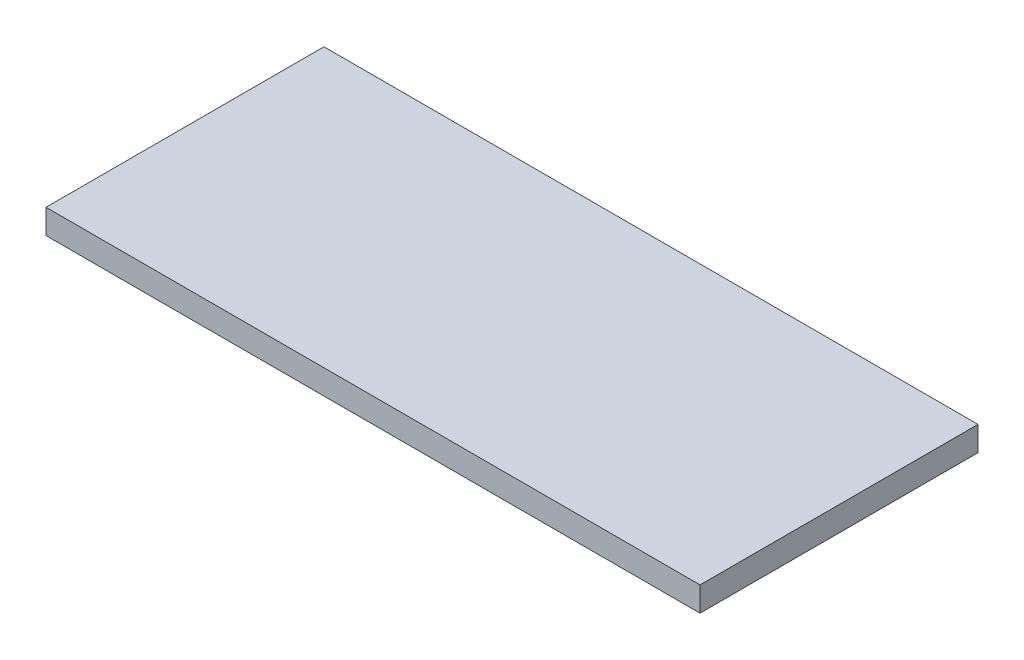
SolidWorks part; units mm, degrees
ref_plane "Front" through (0, 0, 0) normal (0, 0, 1) x (1, 0, 0)
ref_plane "Top" through (0, 0, 0) normal (0, 1, 0) x (1, 0, 0)
ref_plane "Right" through (0, 0, 0) normal (1, 0, 0) x (0, 0, -1)
sketch "Sketch1" plane through (0, 0, 0) normal (0, 1, 0) x (1, 0, 0)
  line L1 (-127, -53.975) -> (127, -53.975)
  line L2 (-127, -53.975) -> (-127, 53.975)
  line L3 (-127, 53.975) -> (127, 53.975)
  line L4 (127, -53.975) -> (127, 53.975)
  line L5 (-127, -53.975) -> (127, 53.975) construction
  line L6 (-127, 53.975) -> (127, -53.975) construction
  point P0 (0, 0)
  dimension "D1" = 107.95
  dimension "D2" = 254
extrude "Boss-Extrude1" add sketch "Sketch1" along normal blind 9.525 contours L4 L3 L2 L1
